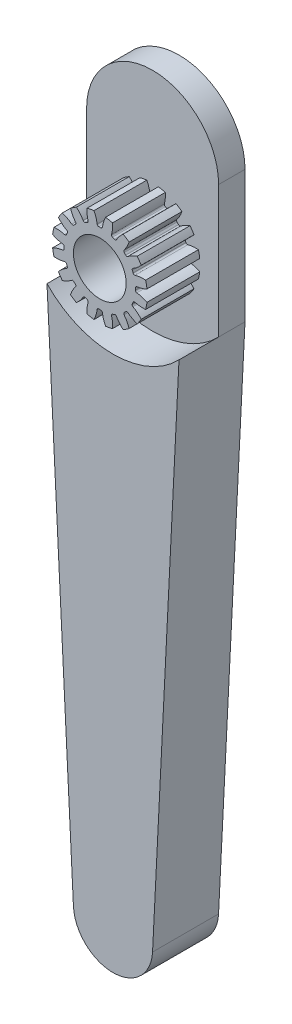
SolidWorks part; units mm, degrees
material "6061 Alloy"
ref_plane "Front Plane" through (0, 0, 0) normal (0, 0, 1) x (1, 0, 0)
ref_plane "Top Plane" through (0, 0, 0) normal (0, 1, 0) x (1, 0, 0)
ref_plane "Right Plane" through (0, 0, 0) normal (1, 0, 0) x (0, 0, -1)
sketch "Sketch1" plane through (0, 0, 0) normal (0, 0, 1) x (1, 0, 0)
  line L0 (0, 0) -> (-50, 0)
  line L1 (-50, 0) -> (-50, -50)
  line L2 (0, 0) -> (0, -50)
  line L3 (-50, -50) -> (-39.9811, -249.2456)
  line L4 (0, -50) -> (-10.0189, -249.2456)
  circle A0 centre (-25, -248.4923) radius 15
  point P15 (-25, 0)
  dimension "D4" = 30
  dimension "D1" = 50
  dimension "D2" = 50
  dimension "D3" = 50
  dimension "D5" = 5.757
extrude "Boss-Extrude1" add sketch "Sketch1" along normal blind 10
sketch "Sketch2" plane through (0, 0, 10) normal (0, 0, 1) x (1, 0, 0)
  line L0 (0, 0) -> (-50, 0) construction
  circle A0 centre (-25, -30) radius 16
  circle A1 centre (-25, -30) radius 18
  circle A2 centre (-25, -30) radius 13.5
  point P5 (-25, 0)
  dimension "D1" = 32
  dimension "D2" = 30
  dimension "D3" = 2
  dimension "D4" = 4.5
extrude "Boss-Extrude2" add sketch "Sketch2" along normal blind 20 contours A1
sketch "Sketch6" plane through (0, 0, 30) normal (0, 0, 1) x (1, 0, 0)
  line L0 (-25, -30) -> (-25, -5.7393) construction
  line L1 (-26.4046, -14.0104) -> (-24.4222, -14.0104) construction
  line L2 (-25, -30) -> (-25.9525, -16.5336) construction
  line L3 (-25, -17.8696) -> (-27.092, -12.122) construction
  line L4 (-25, -30) -> (-21.4884, -12.3459) construction
  arc A0 (-27.184, -12.133) -> (-25.9525, -16.5336) centre (-37.2993, -17.3362) cw
  arc A1 (-22.816, -12.133) -> (-24.0475, -16.5336) centre (-12.7007, -17.3362) ccw
  circle A2 centre (-25, -30) radius 13.5 construction
  arc A3 (-24.0475, -16.5336) -> (-25.9525, -16.5336) centre (-25, -30) ccw
  circle A5 centre (-25, -30) radius 18 construction
  arc A6 (-22.816, -12.133) -> (-27.184, -12.133) centre (-25, -30) ccw
  arc A7 (-27.184, -12.133) -> (-22.816, -12.133) centre (-25, -30) ccw construction
  circle A8 centre (-25, -30) radius 16 construction
  dimension "D2" = 20
  dimension "D3" = 11.25
extrude "Cut-Extrude3" cut sketch "Sketch6" against normal up to surface (20 mm away) up to face at (-7, -30, 10)
fillet "Fillet1" radius 0.6 2 edges at (-24.0475, -16.5336, 20) (-25.9525, -16.5336, 20)
pattern_circular "CirPattern1" count 16 over 360 about axis through (-25, -30, 0) along (0, 0, 1) of "Fillet1", "Cut-Extrude3"
sketch "Sketch8" plane through (0, 0, 10) normal (0, 0, 1) x (1, 0, 0)
  line L5 (-50, -50) -> (-39.9811, -249.2456)
  line L6 (-10.0189, -249.2456) -> (0, -50)
  line L7 (0, -50) -> (0, 0)
  line L8 (0, 0) -> (-50, 0)
  line L9 (-50, 0) -> (-50, -50)
  line L10 (-50, -50) -> (-39.9811, -249.2456)
  line L11 (-10.0189, -249.2456) -> (0, -50)
  arc A0 (-50, -50) -> (0, -50) centre (-25, -25.9107) ccw
  arc A2 (-39.9811, -249.2456) -> (-10.0189, -249.2456) centre (-25, -248.4923) ccw
  arc A3 (-39.9811, -249.2456) -> (-10.0189, -249.2456) centre (-25, -248.4923) ccw
  dimension "D1" = 0
extrude "Boss-Extrude5" add sketch "Sketch8" along normal blind 15 contours A0 L11 A3 L10
sketch "Sketch9" plane through (0, 0, 0) normal (0, 0, -1) x (-1, 0, 0)
  line L0 (0, 0) -> (50, 0)
  arc A0 (0, 0) -> (50, 0) centre (25, 0) cw
extrude "Boss-Extrude6" add sketch "Sketch9" against normal blind 10
sketch "Sketch10" plane through (0, 0, 30) normal (0, 0, 1) x (1, 0, 0)
  circle A0 centre (-25, -30) radius 10
  arc A1 (-24.6076, -16.5057) -> (-25.3924, -16.5057) centre (-25, -30) ccw construction
  arc A2 (-38.4943, -29.6076) -> (-38.4943, -30.3924) centre (-25, -30) ccw construction
  point P6 (-25, -16.5)
  point P13 (-38.5, -30)
  dimension "D1" = 20
extrude "Cut-Extrude4" cut sketch "Sketch10" against normal through all and the other way through all
equation "\"Module\"= 2mm"
equation "\"number teeth\"= 16"
equation "\"D1@Sketch2\"=\"Module\"*\"number teeth\""
equation "\"D4@Sketch2\"=\"Module\"*if( \"Module\"= >1.25,2.25,2.4)"
equation "\"D3@Sketch6\"= 180 /\"number teeth\""
equation "\"D1@Fillet1\"=.3 * \"Module\""
equation "\"D1@CirPattern1\"=\"number teeth\""
